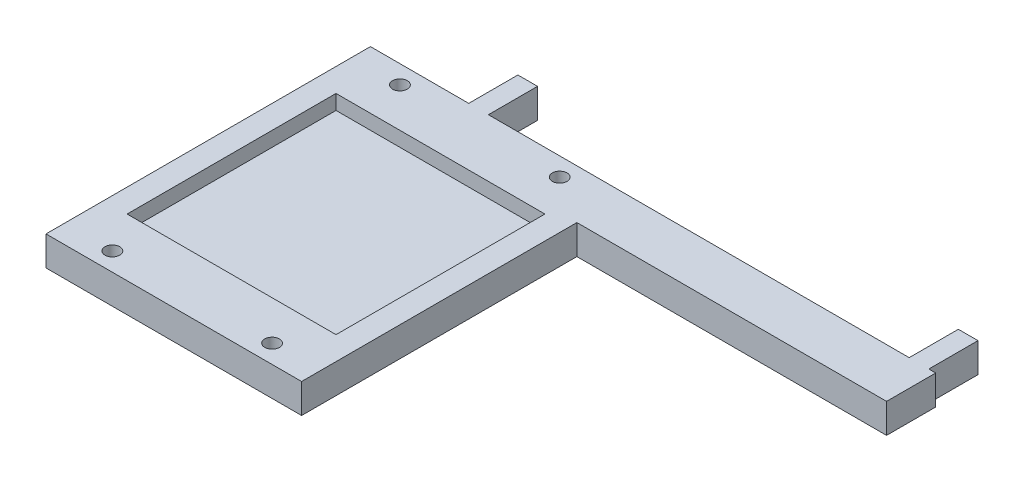
SolidWorks part; units mm, degrees
ref_plane "Front Plane" through (0, 0, 0) normal (0, 0, 1) x (1, 0, 0)
ref_plane "Top Plane" through (0, 0, 0) normal (0, 1, 0) x (1, 0, 0)
ref_plane "Right Plane" through (0, 0, 0) normal (1, 0, 0) x (0, 0, -1)
sketch "Sketch1" plane through (0, 0, 0) normal (0, 1, 0) x (1, 0, 0)
  line L1 (0, 0) -> (-52, 0)
  line L2 (0, 0) -> (0, -66)
  line L3 (0, -66) -> (-52, -66)
  line L4 (-52, 0) -> (-52, -66)
  dimension "D1" = 66
  dimension "D2" = 52
extrude "Boss-Extrude1" add sketch "Sketch1" along normal blind 6
sketch "Sketch2" plane through (0, 6, 0) normal (0, 1, 0) x (1, 0, 0)
  line L0 (-52, 0) -> (-52, -66) construction
  line L1 (-47.25, -11.75) -> (-4.75, -11.75)
  line L2 (-47.25, -11.75) -> (-47.25, -54.25)
  line L3 (-47.25, -54.25) -> (-4.75, -54.25)
  line L4 (-4.75, -11.75) -> (-4.75, -54.25)
  line L5 (-52, -66) -> (0, -66) construction
  point P6 (-47.25, -33)
  point P7 (-52, -33)
  point P8 (-26, -54.25)
  point P11 (-26, -66)
  dimension "D1" = 42.5
  dimension "D2" = 42.5
  dimension "D3" = 0
  dimension "D4" = 0
extrude "Cut-Extrude1" cut sketch "Sketch2" against normal blind 3
sketch "Sketch3" plane through (0, 6, 0) normal (0, 1, 0) x (1, 0, 0)
  line L0 (-4.75, -11.75) -> (-47.25, -11.75) construction
  line L1 (-47.25, -11.75) -> (-47.25, -54.25) construction
  line L2 (-26, 0) -> (-26, -78.9032) construction
  line L3 (0, 0) -> (-52, 0) construction
  line L4 (-52, -33) -> (19.2006, -33) construction
  line L5 (-52, 0) -> (-52, -66) construction
  circle A0 centre (-42.25, -3.75) radius 1.5
  circle A1 centre (-9.75, -3.75) radius 1.5
  circle A2 centre (-9.75, -62.25) radius 1.5
  circle A3 centre (-42.25, -62.25) radius 1.5
  dimension "D1" = 8
  dimension "D2" = 3
  dimension "D3" = 5
extrude "Cut-Extrude2" cut sketch "Sketch3" against normal blind 13
sketch "Sketch4" plane through (0, 0, 0) normal (1, 0, 0) x (0, 0, -1)
  line L0 (-66, 6) -> (0, 6) construction
  line L1 (0, 0) -> (-10, 0)
  line L2 (0, 0) -> (0, 6)
  line L3 (0, 6) -> (-10, 6)
  line L4 (-10, 0) -> (-10, 6)
  dimension "D1" = 10
extrude "Boss-Extrude2" add sketch "Sketch4" along normal blind 63
sketch "Sketch5" plane through (0, 0, 0) normal (0, 0, -1) x (-1, 0, 0)
  line L0 (-63, 6) -> (52, 6) construction
  line L1 (32, 6) -> (28, 6)
  line L2 (32, 6) -> (32, 0)
  line L3 (32, 0) -> (28, 0)
  line L4 (28, 6) -> (28, 0)
  line L5 (-63, 0) -> (52, 0) construction
  line L6 (52, 6) -> (52, 0) construction
  line L8 (-57.6, 6) -> (-61.6, 6)
  line L9 (-57.6, 6) -> (-57.6, 0)
  line L10 (-57.6, 0) -> (-61.6, 0)
  line L11 (-61.6, 6) -> (-61.6, 0)
  dimension "D1" = 4
  dimension "D2" = 20
  dimension "D3" = 4
  dimension "D4" = 85.6
extrude "Boss-Extrude3" add sketch "Sketch5" along normal blind 10
